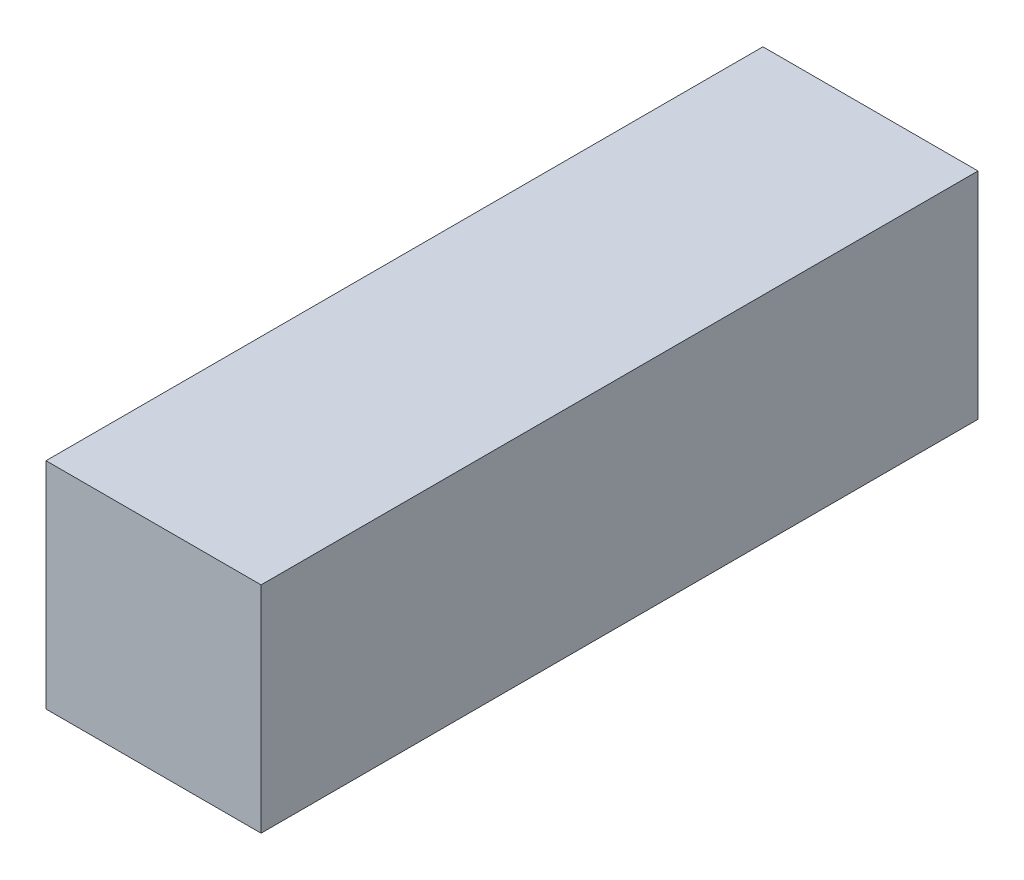
SolidWorks part; units mm, degrees
ref_plane "Front Plane" through (0, 0, 0) normal (0, 0, 1) x (1, 0, 0)
ref_plane "Top Plane" through (0, 0, 0) normal (0, 1, 0) x (1, 0, 0)
ref_plane "Right Plane" through (0, 0, 0) normal (1, 0, 0) x (0, 0, -1)
sketch "Sketch1" plane through (0, 0, 0) normal (0, 0, 1) x (1, 0, 0)
  line L1 (1.5, -1.5) -> (-1.5, -1.5)
  line L2 (1.5, -1.5) -> (1.5, 1.5)
  line L3 (1.5, 1.5) -> (-1.5, 1.5)
  line L4 (-1.5, -1.5) -> (-1.5, 1.5)
  line L5 (1.5, -1.5) -> (-1.5, 1.5) construction
  line L6 (1.5, 1.5) -> (-1.5, -1.5) construction
  point P0 (0, 0)
  dimension "D1" = 3
  dimension "D2" = 3
extrude "Boss-Extrude1" add sketch "Sketch1" along normal blind 10
